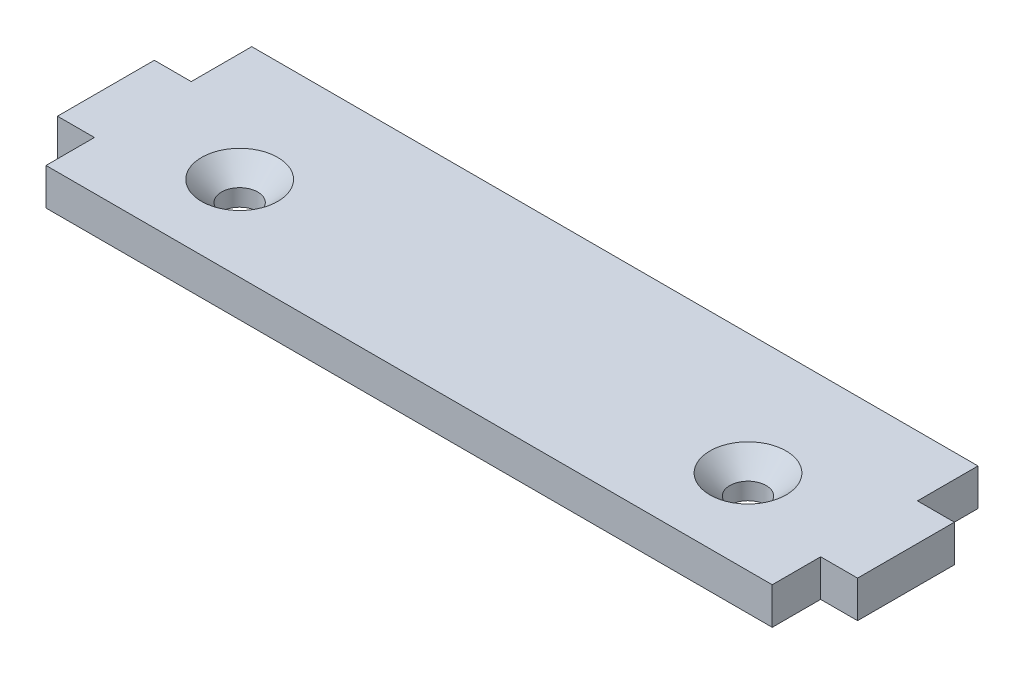
SolidWorks part; units mm, degrees
ref_plane "Front Plane" through (0, 0, 0) normal (0, 0, 1) x (1, 0, 0)
ref_plane "Top Plane" through (0, 0, 0) normal (0, 1, 0) x (1, 0, 0)
ref_plane "Right Plane" through (0, 0, 0) normal (1, 0, 0) x (0, 0, -1)
sketch "Sketch1" plane through (0, 0, 0) normal (0, 1, 0) x (1, 0, 0)
  line L0 (3.05, 12) -> (0, 7)
  line L1 (0, 0) -> (66.1, 0)
  line L2 (0, 0) -> (0, 17)
  line L3 (0, 17) -> (66.1, 17)
  line L4 (66.1, 0) -> (66.1, 17)
  line L7 (0, 12) -> (3.05, 12)
  line L8 (3.05, 17) -> (3.05, 12)
  line L11 (66.1, 12) -> (63.05, 12)
  line L12 (63.05, 17) -> (63.05, 12)
  line L13 (0, 0) -> (12.05, 0)
  line L14 (0, 0) -> (0, 7)
  line L15 (0, 7) -> (12.05, 7)
  line L16 (12.05, 0) -> (12.05, 7)
  line L17 (66.1, 0) -> (54.05, 0)
  line L18 (66.1, 0) -> (66.1, 7)
  line L19 (66.1, 7) -> (54.05, 7)
  line L20 (54.05, 0) -> (54.05, 7)
  line L21 (63.05, 12) -> (66.1, 7)
  line L23 (66.1, 0) -> (63.05, 0)
  line L24 (66.1, 0) -> (66.1, 4)
  line L25 (66.1, 4) -> (63.05, 4)
  line L26 (63.05, 0) -> (63.05, 4)
  line L27 (0, 0) -> (3.05, 0)
  line L28 (0, 0) -> (0, 4)
  line L29 (0, 4) -> (3.05, 4)
  line L30 (3.05, 0) -> (3.05, 4)
  circle A0 centre (12.05, 7) radius 1.5
  circle A1 centre (54.05, 7) radius 1.5
  dimension "D9" = 3
  dimension "D12" = 3
  dimension "D1" = 17
  dimension "D2" = 66.1
  dimension "D3" = 5
  dimension "D4" = 3.05
  dimension "D5" = 5
  dimension "D6" = 3.05
  dimension "D7" = 12.05
  dimension "D8" = 7
  dimension "D10" = 7
  dimension "D11" = 12.05
  dimension "D13" = 5
  dimension "D14" = 58.617
  dimension "D15" = 5
  dimension "D16" = 58.617
  dimension "D17" = 4
  dimension "D18" = 3.05
  dimension "D19" = 4
  dimension "D20" = 3.05
extrude "Boss-Extrude1" add sketch "Sketch1" along normal blind 3.05 contours L12 L3 L8 L7 L2 L1 L4 L11 | A0 L15 L2 L1 L16 | A1 L20 L1 L4 L19 | L11 L21 L4 | L7 L2 L0
hole_wizard "CSK for M3 Flat Head Machine Screw1" positions "Sketch4" profile "Sketch5" countersink size "M3" standard "ANSI Metric" end condition through all
sketch "Sketch4" plane through (0, 3.05, 0) normal (0, 1, 0) x (1, 0, 0)
  point P0 (12.05, 7)
sketch "Sketch5" plane through (12.05, 3.05, -7) normal (1, 0, 0) x (0, 0, 1)
  line L0 (0, 0) -> (0, 3.05)
  line L1 (0, 3.05) -> (1.5, 3.05)
  line L2 (1.5, 3.05) -> (1.5, 1.65)
  line L3 (1.5, 1.65) -> (3.15, 0)
  line L5 (3.15, 0) -> (0, 0)
  line L6 (-1.5, 1.65) -> (-3.15, 0) construction
  line L11 (0, -6.35) -> (0, 107.95) construction
  dimension "Thru Hole Dia." = 3
  dimension "Thru Hole Depth" = 3.05
  dimension "Near C'Sink Dia." = 6.3
  dimension "Near C'Sink Angle" = 90
hole_wizard "CSK for M3 Flat Head Machine Screw2" positions "Sketch6" profile "Sketch7" countersink size "M3" standard "ANSI Metric" end condition through all
sketch "Sketch6" plane through (0, 3.05, 0) normal (0, 1, 0) x (1, 0, 0)
  point P0 (54.05, 7)
sketch "Sketch7" plane through (54.05, 3.05, -7) normal (1, 0, 0) x (0, 0, 1)
  line L0 (0, 0) -> (0, 3.05)
  line L1 (0, 3.05) -> (1.5, 3.05)
  line L2 (1.5, 3.05) -> (1.5, 1.65)
  line L3 (1.5, 1.65) -> (3.15, 0)
  line L5 (3.15, 0) -> (0, 0)
  line L6 (-1.5, 1.65) -> (-3.15, 0) construction
  line L11 (0, -6.35) -> (0, 107.95) construction
  dimension "Thru Hole Dia." = 3
  dimension "Thru Hole Depth" = 3.05
  dimension "Near C'Sink Dia." = 6.3
  dimension "Near C'Sink Angle" = 90
